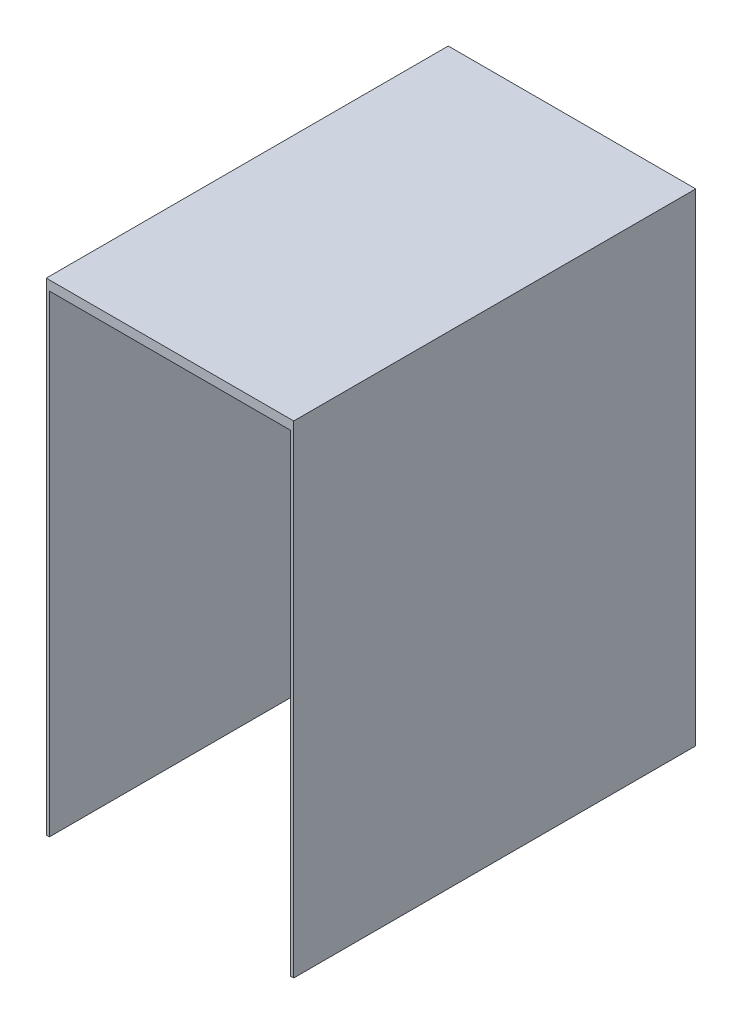
SolidWorks part; units mm, degrees
ref_plane "Front" through (0, 0, 0) normal (0, 0, 1) x (1, 0, 0)
ref_plane "Top" through (0, 0, 0) normal (0, 1, 0) x (1, 0, 0)
ref_plane "Right" through (0, 0, 0) normal (1, 0, 0) x (0, 0, -1)
sketch "Sketch1" plane through (0, 0, 0) normal (0, 0, 1) x (1, 0, 0)
  line L0 (0, 0) -> (0, 152.4)
  line L1 (0, 152.4) -> (78.1812, 152.4)
  line L2 (78.1812, 152.4) -> (78.1812, 0)
  line L3 (78.1812, 0) -> (77.1906, 0)
  line L4 (77.1906, 0) -> (77.1906, 149.352)
  line L5 (77.1906, 149.352) -> (0.9906, 149.352)
  line L6 (0.9906, 149.352) -> (0.9906, 0)
  line L7 (0.9906, 0) -> (0, 0)
  dimension "D1" = 152.4
  dimension "D2" = 0.9906
  dimension "D3" = 0.9906
  dimension "D4" = 3.048
  dimension "D5" = 76.2
extrude "Boss-Extrude2" add sketch "Sketch1" along normal blind 127
